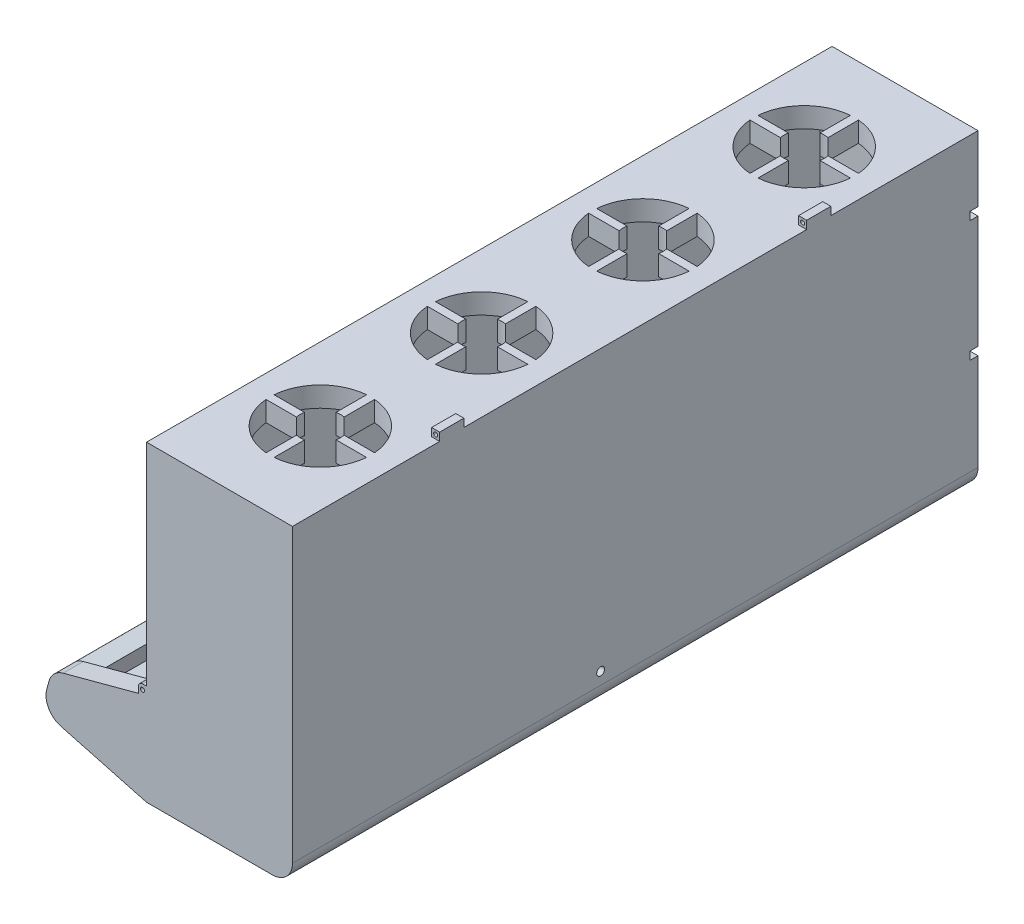
SolidWorks part; units mm, degrees
ref_plane "Front Plane" through (0, 0, 0) normal (0, 0, 1) x (1, 0, 0)
ref_plane "Top Plane" through (0, 0, 0) normal (0, 1, 0) x (1, 0, 0)
ref_plane "Right Plane" through (0, 0, 0) normal (1, 0, 0) x (0, 0, -1)
sketch "Sketch1" plane through (0, 0, 0) normal (0, 0, 1) x (1, 0, 0)
  line L16 (0, 0) -> (0, 25)
  line L17 (0, 25) -> (-15.5956, 25)
  line L18 (0, 0) -> (-15.5956, -9.0041)
  line L19 (-15.5956, 25) -> (-15.5956, 27.5)
  line L20 (-15.5956, 27.5) -> (2.5, 27.5)
  line L21 (2.5, 27.5) -> (2.5, -1.4434)
  line L22 (2.5, -1.4434) -> (-14.3456, -11.1692)
  line L23 (-14.3456, -11.1692) -> (-15.5956, -9.0041)
  line L24 (-15.5956, -9.0041) -> (-15.5956, 25) construction
  dimension "D1" = 25
  dimension "D2" = 120
  dimension "D3" = 2.5
  dimension "D4" = 2.5
  dimension "D5" = 2.5
extrude "Boss-Extrude1" add sketch "Sketch1" along normal blind 80
sketch "Sketch2" plane through (0, 27.5, 0) normal (0, 1, 0) x (1, 0, 0)
  line L0 (-6.5478, -10) -> (-6.5478, 0) construction
  line L1 (2.5, 0) -> (-15.5956, 0) construction
  line L2 (2.5, -80) -> (-15.5956, -80) construction
  circle A0 centre (-6.5478, -10) radius 2.5
  circle A1 centre (-6.5478, -30) radius 2.5
  circle A2 centre (-6.5478, -50) radius 2.5
  circle A3 centre (-6.5478, -70) radius 2.5
  dimension "D1" = 5
  dimension "D2" = 10
  dimension "D4" = 10
  dimension "D3" = 4
extrude "Cut-Extrude1" cut sketch "Sketch2" against normal up to surface (2.5 mm away) up to face at (-7.7978, 25, 40)
sketch "Sketch3" plane through (0, 0, 0) normal (0, 0, -1) x (-1, 0, 0)
  line L0 (15.5956, 25) -> (15.5956, -9.0041)
  line L1 (15.5956, -9.0041) -> (15.5956, -11.1692)
  line L2 (15.5956, -11.1692) -> (14.3456, -11.1692)
  line L8 (15.5956, -9.0041) -> (0, 0)
  line L9 (0, 0) -> (0, 25)
  line L10 (0, 25) -> (15.5956, 25)
  line L11 (15.5956, 25) -> (15.5956, 27.5)
  line L12 (15.5956, 27.5) -> (-2.5, 27.5)
  line L13 (-2.5, 27.5) -> (-2.5, -1.4434)
  line L14 (-2.5, -1.4434) -> (14.3456, -11.1692)
  line L15 (14.3456, -11.1692) -> (15.5956, -9.0041)
  line L19 (15.5956, 25) -> (15.5956, 27.5)
  line L20 (15.5956, 27.5) -> (-2.5, 27.5)
  line L21 (-2.5, 27.5) -> (-2.5, -1.4434)
  line L22 (-2.5, -1.4434) -> (14.3456, -11.1692)
  dimension "D1" = 0
extrude "Boss-Extrude2" add sketch "Sketch3" along normal blind 2.5
sketch "Sketch4" plane through (0, 0, 80) normal (0, 0, 1) x (1, 0, 0)
  line L0 (-15.5956, 25) -> (-15.5956, -9.0041)
  line L1 (-15.5956, -9.0041) -> (-15.5956, -11.1692)
  line L2 (-15.5956, -11.1692) -> (-14.3456, -11.1692)
  line L8 (0, 0) -> (-15.5956, -9.0041)
  line L9 (-15.5956, -9.0041) -> (-14.3456, -11.1692)
  line L10 (-14.3456, -11.1692) -> (2.5, -1.4434)
  line L11 (2.5, -1.4434) -> (2.5, 27.5)
  line L12 (2.5, 27.5) -> (-15.5956, 27.5)
  line L13 (-15.5956, 27.5) -> (-15.5956, 25)
  line L14 (-15.5956, 25) -> (0, 25)
  line L15 (0, 25) -> (0, 0)
  line L18 (-14.3456, -11.1692) -> (2.5, -1.4434)
  line L19 (2.5, -1.4434) -> (2.5, 27.5)
  line L20 (2.5, 27.5) -> (-15.5956, 27.5)
  line L21 (-15.5956, 27.5) -> (-15.5956, 25)
  dimension "D1" = 0
extrude "Boss-Extrude3" add sketch "Sketch4" along normal blind 2.5
sketch "Sketch6" plane through (0, 0, -2.5) normal (0, 0, -1) x (-1, 0, 0)
  line L0 (14.3456, -11.1692) -> (-2.5, -11.1692)
  line L1 (-2.5, -11.1692) -> (-2.5, -1.4434)
  line L2 (14.3456, -11.1692) -> (-2.5, -1.4434)
extrude "Boss-Extrude4" add sketch "Sketch6" against normal blind 2.5
sketch "Sketch7" plane through (0, 0, 82.5) normal (0, 0, 1) x (1, 0, 0)
  line L3 (2.5, -1.4434) -> (-14.3456, -11.1692)
  line L4 (-14.3456, -11.1692) -> (2.5, -11.1692)
  line L5 (2.5, -11.1692) -> (2.5, -1.4434)
  line L6 (2.5, -1.4434) -> (-14.3456, -11.1692)
  line L7 (-14.3456, -11.1692) -> (2.5, -11.1692)
  line L8 (2.5, -11.1692) -> (2.5, -1.4434)
  dimension "D1" = 0
extrude "Boss-Extrude5" add sketch "Sketch7" against normal blind 2.5
sketch "Sketch9" plane through (0, -11.1692, 0) normal (0, -1, 0) x (1, 0, 0)
  line L1 (-14.3456, -2.5) -> (2.5, -2.5)
  line L2 (-14.3456, -2.5) -> (-14.3456, 82.5)
  line L3 (-14.3456, 82.5) -> (2.5, 82.5)
  line L4 (2.5, -2.5) -> (2.5, 82.5)
extrude "Boss-Extrude10" add sketch "Sketch9" against normal blind 2.5
sketch "Sketch10" plane through (0, -8.6692, 0) normal (0, 1, 0) x (1, 0, 0)
  line L0 (-2.6549, -0.606) -> (-0.5, -0.606)
  line L1 (-3.1549, -0.106) -> (0, -0.106)
  line L2 (-3.1549, -0.106) -> (-3.1549, -41.3652)
  line L3 (-3.1549, -41.3652) -> (0, -41.3652)
  line L4 (0, -0.106) -> (0, -41.3652)
  line L17 (-0.5, -0.606) -> (-0.5, -40.8652)
  line L18 (-2.6549, -40.8652) -> (-0.5, -40.8652)
  line L19 (-2.6549, -0.606) -> (-2.6549, -40.8652)
  dimension "D1" = 0.5
sketch "Sketch12" plane through (0, 27.5, 0) normal (0, 1, 0) x (1, 0, 0)
  line L4 (2.5, -82.5) -> (2.5, 2.5)
  line L5 (2.5, 2.5) -> (-15.5956, 2.5)
  line L6 (-15.5956, 2.5) -> (-15.5956, -82.5)
  line L7 (-15.5956, -82.5) -> (2.5, -82.5)
  line L8 (2.5, -82.5) -> (2.5, 2.5)
  line L9 (2.5, 2.5) -> (-15.5956, 2.5)
  line L10 (-15.5956, 2.5) -> (-15.5956, -82.5)
  line L11 (-15.5956, -82.5) -> (2.5, -82.5)
  line L16 (0.5, -80.5) -> (0.5, 0.5)
  line L17 (0.5, 0.5) -> (-13.5956, 0.5)
  line L18 (-13.5956, 0.5) -> (-13.5956, -80.5)
  line L19 (-13.5956, -80.5) -> (0.5, -80.5)
  line L20 (0.5, -80.5) -> (0.5, 0.5)
  line L21 (0.5, 0.5) -> (-13.5956, 0.5)
  line L22 (-13.5956, 0.5) -> (-13.5956, -80.5)
  line L23 (-13.5956, -80.5) -> (0.5, -80.5)
  dimension "D1" = 0
  dimension "D2" = 2
extrude "Boss-Extrude13" add sketch "Sketch12" along normal blind 12.5
sketch "Sketch13" plane through (0, 40, 0) normal (0, 1, 0) x (1, 0, 0)
  line L4 (-15.5956, -82.5) -> (2.5, -82.5)
  line L5 (2.5, -82.5) -> (2.5, 2.5)
  line L6 (2.5, 2.5) -> (-15.5956, 2.5)
  line L7 (-15.5956, 2.5) -> (-15.5956, -82.5)
  line L8 (-15.5956, -82.5) -> (2.5, -82.5)
  line L9 (2.5, -82.5) -> (2.5, 2.5)
  line L10 (2.5, 2.5) -> (-15.5956, 2.5)
  line L11 (-15.5956, 2.5) -> (-15.5956, -82.5)
  dimension "D1" = 0
extrude "Boss-Extrude14" add sketch "Sketch13" along normal blind 2.5
sketch "Sketch15" plane through (0, 0, 80) normal (0, 0, -1) x (-1, 0, 0)
  line L3 (15.5956, -11.1692) -> (15.5956, -9.0041)
  line L4 (15.5956, -9.0041) -> (14.3456, -11.1692)
  line L5 (14.3456, -11.1692) -> (15.5956, -11.1692)
  line L6 (15.5956, -11.1692) -> (15.5956, -9.0041)
  line L7 (15.5956, -9.0041) -> (14.3456, -11.1692)
  line L8 (14.3456, -11.1692) -> (15.5956, -11.1692)
  dimension "D1" = 0
extrude "Boss-Extrude15" add sketch "Sketch15" along normal up to surface (80 mm away) up to face at (-7.7978, 10.249, 0)
sketch "Sketch16" plane through (0, 0, -2.5) normal (0, 0, -1) x (-1, 0, 0)
  line L0 (15.5956, -11.1692) -> (28.6248, -7.678)
  line L1 (28.6248, -7.678) -> (27.9778, -5.2632)
  line L2 (27.9778, -5.2632) -> (15.5956, -8.581)
  line L3 (15.5956, -8.581) -> (15.5956, -11.1692)
  line L4 (15.5956, -11.1692) -> (15.5956, 42.5) construction
  dimension "D1" = 2.5
  dimension "D2" = 75
extrude "Boss-Extrude16" add sketch "Sketch16" against normal up to surface (85 mm away)
sketch "Sketch17" plane through (0, 0, -2.5) normal (0, 0, -1) x (-1, 0, 0)
  line L0 (27.9778, -5.2632) -> (27.3307, -2.8484)
  line L1 (27.3307, -2.8484) -> (24.9159, -3.4954)
  line L2 (24.9159, -3.4954) -> (25.563, -5.9102)
  line L3 (27.9778, -5.2632) -> (15.5956, -8.581) construction
  line L4 (25.563, -5.9102) -> (27.9778, -5.2632)
  line L5 (28.6248, -7.678) -> (27.9778, -5.2632) construction
  dimension "D1" = 2.5
  dimension "D2" = 2.5
extrude "Boss-Extrude17" add sketch "Sketch17" against normal up to surface (85 mm away)
sketch "Sketch18" plane through (0, 0, -2.5) normal (0, 0, -1) x (-1, 0, 0)
  line L0 (27.3307, -2.8484) -> (15.5956, 0.296)
  line L1 (15.5956, -8.581) -> (15.5956, 42.5) construction
  line L2 (15.5956, 0.296) -> (15.5956, -8.581)
  line L3 (15.5956, -8.581) -> (25.563, -5.9102)
  line L4 (25.563, -5.9102) -> (24.9159, -3.4954)
  line L5 (24.9159, -3.4954) -> (27.3307, -2.8484)
  dimension "D1" = 75
extrude "Boss-Extrude18" add sketch "Sketch18" against normal blind 2.5
sketch "Sketch19" plane through (0, 0, 82.5) normal (0, 0, 1) x (1, 0, 0)
  line L5 (-15.5956, 0.296) -> (-27.3307, -2.8484)
  line L6 (-15.5956, -8.581) -> (-15.5956, 0.296)
  line L7 (-25.563, -5.9102) -> (-15.5956, -8.581)
  line L8 (-24.9159, -3.4954) -> (-25.563, -5.9102)
  line L9 (-27.3307, -2.8484) -> (-24.9159, -3.4954)
  line L10 (-15.5956, 0.296) -> (-27.3307, -2.8484)
  line L11 (-15.5956, -8.581) -> (-15.5956, 0.296)
  line L12 (-25.563, -5.9102) -> (-15.5956, -8.581)
  line L13 (-24.9159, -3.4954) -> (-25.563, -5.9102)
  line L14 (-27.3307, -2.8484) -> (-24.9159, -3.4954)
  dimension "D1" = 0
extrude "Boss-Extrude19" add sketch "Sketch19" against normal blind 2.5
extrude "Boss-Extrude21" add sketch "Sketch10" along normal blind 2.5
sketch "Sketch23" plane through (0, -6.1692, 0) normal (0, 1, 0) x (1, 0, 0)
  line L4 (-3.1549, -0.106) -> (-3.1549, -41.3652)
  line L5 (-3.1549, -41.3652) -> (0, -41.3652)
  line L6 (0, -41.3652) -> (0, -0.106)
  line L7 (0, -0.106) -> (-3.1549, -0.106)
  line L8 (-3.1549, -0.106) -> (-3.1549, -41.3652)
  line L9 (-3.1549, -41.3652) -> (0, -41.3652)
  line L10 (0, -41.3652) -> (0, -0.106)
  line L11 (0, -0.106) -> (-3.1549, -0.106)
  dimension "D1" = 0
extrude "Boss-Extrude22" add sketch "Sketch23" along normal blind 0.5
sketch "Sketch24" plane through (0, 0, 0) normal (1, 0, 0) x (0, 0, -1)
  line L4 (-41.3652, -8.6692) -> (-0.106, -8.6692)
  line L5 (-0.106, -8.6692) -> (-0.106, -5.6692)
  line L6 (-0.106, -5.6692) -> (-41.3652, -5.6692)
  line L7 (-41.3652, -5.6692) -> (-41.3652, -8.6692)
  line L8 (-41.3652, -8.6692) -> (-0.106, -8.6692)
  line L9 (-0.106, -8.6692) -> (-0.106, -5.6692)
  line L10 (-0.106, -5.6692) -> (-41.3652, -5.6692)
  line L11 (-41.3652, -5.6692) -> (-41.3652, -8.6692)
  dimension "D1" = 0
extrude "Cut-Extrude4" cut sketch "Sketch24" against normal blind 0.5
sketch "Sketch25" plane through (-2.6549, 0, 0) normal (1, 0, 0) x (0, 0, -1)
  line L0 (-40.8652, -6.1692) -> (-40.8652, -8.6692) construction
  line L1 (-0.606, -8.6692) -> (-40.8652, -8.6692)
  line L2 (-0.606, -8.6692) -> (-0.606, -8.1692)
  line L3 (-0.606, -8.1692) -> (-40.8652, -8.1692)
  line L4 (-40.8652, -8.6692) -> (-40.8652, -8.1692)
  dimension "D1" = 0.5
extrude "Boss-Extrude23" add sketch "Sketch25" along normal up to surface (2.1549 mm away) up to face at (-0.5, -7.2942, 20.7356)
sketch "Sketch26" plane through (-0.5, 0, 0) normal (1, 0, 0) x (0, 0, -1)
  line L0 (-20.7356, -6.1692) -> (-20.7356, -8.1692) construction
  line L1 (-0.606, -6.1692) -> (-40.8652, -6.1692) construction
  line L2 (-0.606, -8.1692) -> (-40.8652, -8.1692) construction
  line L4 (-20.9278, -8.1692) -> (-20.5158, -8.1692)
  line L5 (-20.9278, -8.1692) -> (-20.9278, -7.9938)
  line L6 (-20.9278, -7.9938) -> (-20.5158, -7.9938)
  line L7 (-20.5158, -8.1692) -> (-20.5158, -7.9938)
extrude "Boss-Extrude24" add sketch "Sketch26" against normal up to surface (2.1549 mm away) up to face at (-2.6549, -7.1692, 20.7356)
sketch "Sketch27" plane through (0, 0, 0.606) normal (0, 0, 1) x (1, 0, 0)
  circle A0 centre (-1.1714, -7.4121) radius 0.5386
extrude "Boss-Extrude25" add sketch "Sketch27" along normal blind 0.25
sketch "Sketch28" plane through (0, 0, 40.8652) normal (0, 0, -1) x (-1, 0, 0)
  line L1 (0.411, -6.8481) -> (1.6695, -6.8481)
  line L2 (0.411, -6.8481) -> (0.411, -7.9194)
  line L3 (0.411, -7.9194) -> (1.6695, -7.9194)
  line L4 (1.6695, -6.8481) -> (1.6695, -7.9194)
extrude "Boss-Extrude26" add sketch "Sketch28" along normal blind 0.25
sketch "Sketch29" plane through (-0.5, 0, 0) normal (1, 0, 0) x (0, 0, -1)
  line L0 (-0.606, -6.1692) -> (-40.8652, -6.1692)
  line L1 (-40.8652, -6.1692) -> (-40.8652, -8.1692)
  line L2 (-40.8652, -8.1692) -> (-0.606, -8.1692)
  line L3 (-0.606, -8.1692) -> (-0.606, -6.1692)
  line L4 (-41.3652, -8.6692) -> (-0.106, -8.6692)
  line L5 (-0.106, -8.6692) -> (-0.106, -5.6692)
  line L6 (-0.106, -5.6692) -> (-41.3652, -5.6692)
  line L7 (-41.3652, -5.6692) -> (-41.3652, -8.6692)
  line L8 (-41.3652, -8.6692) -> (-0.106, -8.6692)
  line L9 (-0.106, -8.6692) -> (-0.106, -5.6692)
  line L10 (-0.106, -5.6692) -> (-41.3652, -5.6692)
  line L11 (-41.3652, -5.6692) -> (-41.3652, -8.6692)
  dimension "D1" = 0
  dimension "D2" = 0.5
extrude "Boss-Extrude27" add sketch "Sketch29" along normal blind 1.25
sketch "Sketch31" plane through (2.5, 0, 0) normal (1, 0, 0) x (0, 0, -1)
  line L1 (-80, -1.4434) -> (0, -1.4434)
  line L2 (-80, -1.4434) -> (-80, -8.6692)
  line L3 (-80, -8.6692) -> (0, -8.6692)
  line L4 (0, -1.4434) -> (0, -8.6692)
sketch "Sketch32" plane through (0, -8.6692, 0) normal (0, 1, 0) x (1, 0, 0)
  line L1 (-5.5507, -49.6825) -> (0, -49.6825)
  line L2 (-5.5507, -49.6825) -> (-5.5507, -76.0243)
  line L3 (-5.5507, -76.0243) -> (0, -76.0243)
  line L4 (0, -49.6825) -> (0, -76.0243)
extrude "Boss-Extrude28" add sketch "Sketch32" along normal blind 0.5
sketch "Sketch33" plane through (0, -8.1692, 0) normal (0, 1, 0) x (1, 0, 0)
  line L1 (-3.0223, -50.6363) -> (-1.4068, -50.6363)
  line L2 (-3.0223, -50.6363) -> (-3.0223, -53.4267)
  line L3 (-3.0223, -53.4267) -> (-1.4068, -53.4267)
  line L4 (-1.4068, -50.6363) -> (-1.4068, -53.4267)
  line L5 (-3.0223, -54.6751) -> (-1.4068, -54.6751)
  line L6 (-3.0223, -54.6751) -> (-3.0223, -58.4937)
  line L7 (-3.0223, -58.4937) -> (-1.4068, -58.4937)
  line L8 (-1.4068, -54.6751) -> (-1.4068, -58.4937)
  line L9 (-3.0223, -60.2561) -> (-1.4068, -60.2561)
  line L10 (-3.0223, -60.2561) -> (-3.0223, -64.4418)
  line L11 (-3.0223, -64.4418) -> (-1.4068, -64.4418)
  line L12 (-1.4068, -60.2561) -> (-1.4068, -64.4418)
  line L13 (-3.0223, -66.5714) -> (-1.4068, -66.5714)
  line L14 (-3.0223, -66.5714) -> (-3.0223, -70.2431)
  line L15 (-3.0223, -70.2431) -> (-1.4068, -70.2431)
  line L16 (-1.4068, -66.5714) -> (-1.4068, -70.2431)
extrude "Boss-Extrude29" add sketch "Sketch33" along normal blind 0.25
extrude "Boss-Extrude30" add sketch "Sketch31" against normal blind 0.25
sketch "Sketch34" plane through (0, 0, 0) normal (0, 0, 1) x (1, 0, 0)
  line L1 (-15.5956, 25) -> (-14.5956, 25)
  line L2 (-15.5956, 25) -> (-15.5956, 0.296)
  line L3 (-15.5956, 0.296) -> (-14.5956, 0.296)
  line L4 (-14.5956, 25) -> (-14.5956, 0.296)
  dimension "D1" = 1
extrude "Boss-Extrude31" add sketch "Sketch34" along normal up to surface (80 mm away) separate body up to face at (-15.5769, 2.273, 80)
sketch "Sketch38" plane through (0, 0, -2.5) normal (0, 0, -1) x (-1, 0, 0)
  line L0 (-2.5, 40) -> (-2.5, 42.5)
  line L1 (-2.5, 42.5) -> (-2.5, -11.1692) construction
  line L2 (-2.5, 42.5) -> (0, 42.5)
  line L3 (-2.5, 42.5) -> (15.5956, 42.5) construction
  line L4 (13.0956, 42.5) -> (15.5956, 42.5)
  line L5 (15.5956, 42.5) -> (15.5956, 40)
  line L6 (15.5956, 0.296) -> (15.5956, 42.5) construction
  line L7 (26.21, -8.3251) -> (28.6248, -7.678)
  line L8 (15.5956, -11.1692) -> (28.6248, -7.678) construction
  line L9 (28.6248, -7.678) -> (27.9778, -5.2632)
  line L10 (28.6248, -7.678) -> (27.3307, -2.8484) construction
  line L11 (25.9365, -2.4748) -> (27.3307, -2.8484)
  line L12 (27.3307, -2.8484) -> (15.5956, 0.296) construction
  line L13 (27.3307, -2.8484) -> (27.7043, -4.2426)
  arc A0 (0, 42.5) -> (-2.5, 40) centre (0, 40) ccw
  arc A1 (15.5956, 40) -> (13.0956, 42.5) centre (13.0956, 40) ccw
  arc A2 (27.9778, -5.2632) -> (26.21, -8.3251) centre (25.563, -5.9102) cw
  arc A3 (27.7043, -4.2426) -> (25.9365, -2.4748) centre (25.2895, -4.8896) ccw
  dimension "D1" = 2.5
  dimension "D2" = 2.5
  dimension "D3" = 2.5
  dimension "D4" = 2.5
extrude "Cut-Extrude6" cut sketch "Sketch38" against normal up to surface (85 mm away) up to face at (-13.9632, 7.4902, 82.5)
sketch "Sketch39" plane through (0, 0, -2.5) normal (0, 0, -1) x (-1, 0, 0)
  line L0 (-2.5, 27.5) -> (15.5956, 27.5)
  line L7 (13.0956, 42.5) -> (0, 42.5)
  line L8 (-2.5, 40) -> (-2.5, -11.1692)
  line L9 (-2.5, -11.1692) -> (15.5956, -11.1692)
  line L10 (15.5956, -11.1692) -> (26.21, -8.3251)
  line L11 (27.9778, -5.2632) -> (27.7043, -4.2426)
  line L12 (25.9365, -2.4748) -> (15.5956, 0.296)
  line L13 (15.5956, 0.296) -> (15.5956, 40)
  line L14 (13.0956, 42.5) -> (0, 42.5)
  line L15 (-2.5, 40) -> (-2.5, 27.5)
  line L20 (15.5956, 27.5) -> (15.5956, 40)
  arc A4 (0, 42.5) -> (-2.5, 40) centre (0, 40) ccw
  arc A5 (26.21, -8.3251) -> (27.9778, -5.2632) centre (25.563, -5.9102) ccw
  arc A6 (27.7043, -4.2426) -> (25.9365, -2.4748) centre (25.2895, -4.8896) ccw
  arc A7 (15.5956, 40) -> (13.0956, 42.5) centre (13.0956, 40) ccw
  arc A8 (0, 42.5) -> (-2.5, 40) centre (0, 40) ccw
  arc A11 (15.5956, 40) -> (13.0956, 42.5) centre (13.0956, 40) ccw
  dimension "D2" = 15
  dimension "D1" = 0
extrude "Cut-Extrude7" cut sketch "Sketch39" against normal up to surface (85 mm away) up to face at (-14.8711, 11.2326, 82.5)
sketch "Sketch40" plane through (2.5, 0, 0) normal (1, 0, 0) x (0, 0, -1)
  line L5 (-82.5, 27.5) -> (2.5, 27.5) construction
  line L10 (-64.25, 28.5) -> (-61.25, 28.5)
  line L11 (-64.25, 28.5) -> (-64.25, 27.5)
  line L12 (-64.25, 27.5) -> (-61.25, 27.5)
  line L13 (-61.25, 28.5) -> (-61.25, 27.5)
  line L14 (-61.25, 28.5) -> (-18.75, 28.5) construction
  line L15 (-18.75, 28.5) -> (-15.75, 28.5)
  line L16 (-18.75, 28.5) -> (-18.75, 27.5)
  line L17 (-18.75, 27.5) -> (-15.75, 27.5)
  line L18 (-15.75, 28.5) -> (-15.75, 27.5)
  line L19 (-40, 27.5) -> (-40, 28.5) construction
  dimension "D1" = 1
  dimension "D2" = 3
  dimension "D3" = 3
  dimension "D4" = 42.5
extrude "Boss-Extrude32" add sketch "Sketch40" against normal blind 1
sketch "Sketch41" plane through (0, 0, 15.75) normal (0, 0, -1) x (-1, 0, 0)
  line L0 (-2.5, 28) -> (-2, 28) construction
  line L1 (-2.5, 27.5) -> (-2.5, 28.5) construction
  line L2 (-2, 28) -> (-2, 28.5) construction
  line L3 (-1.5, 28.5) -> (-2.5, 28.5) construction
  circle A0 centre (-2, 28) radius 0.25
  dimension "D1" = 0.5
extrude "Cut-Extrude8" cut sketch "Sketch41" against normal up to surface (48.5 mm away) up to face at (2, 28, 64.25)
sketch "Sketch42" plane through (0, 27.5, 0) normal (0, 1, 0) x (1, 0, 0)
  line L0 (-6.5478, -16.25) -> (-6.5478, -12.5) construction
  line L1 (2.5, 2.5) -> (-15.5956, 2.5) construction
  line L2 (-12.7978, -10) -> (-9.0478, -10) construction
  line L4 (-7.0478, -3.77) -> (-7.0478, -7.5505)
  line L6 (-6.0478, -3.77) -> (-6.0478, -7.5505)
  line L7 (-12.7778, -9.5) -> (-8.9973, -9.5)
  line L9 (-12.7778, -10.5) -> (-8.9973, -10.5)
  line L11 (-12.7778, -29.5) -> (-8.9973, -29.5)
  line L12 (-6.0478, -32.4495) -> (-6.0478, -36.23)
  line L13 (-12.7778, -30.5) -> (-8.9973, -30.5)
  line L14 (-7.0478, -23.77) -> (-7.0478, -27.5505)
  line L15 (-6.0478, -23.77) -> (-6.0478, -27.5505)
  line L16 (-12.7778, -49.5) -> (-8.9973, -49.5)
  line L17 (-4.0478, -70) -> (-0.2978, -70) construction
  line L18 (-12.7778, -50.5) -> (-8.9973, -50.5)
  line L19 (-7.0478, -43.77) -> (-7.0478, -47.5505)
  line L20 (-6.0478, -43.77) -> (-6.0478, -47.5505)
  line L21 (-12.7778, -69.5) -> (-8.9973, -69.5)
  line L22 (-12.7978, -70) -> (-9.0478, -70) construction
  line L23 (-12.7778, -70.5) -> (-8.9973, -70.5)
  line L24 (-7.0478, -63.77) -> (-7.0478, -67.5505)
  line L25 (-6.0478, -63.77) -> (-6.0478, -67.5505)
  line L26 (2.5, -82.5) -> (-15.5956, -82.5) construction
  line L27 (-4.0983, -29.5) -> (-0.3178, -29.5)
  line L28 (-7.0478, -30) -> (-6.0478, -30) construction
  line L29 (-4.0983, -30.5) -> (-0.3178, -30.5)
  line L30 (-7.0478, -32.4495) -> (-7.0478, -36.23)
  line L31 (-4.0983, -9.5) -> (-0.3178, -9.5)
  line L32 (-4.0478, -10) -> (-0.2978, -10) construction
  line L33 (-4.0983, -10.5) -> (-0.3178, -10.5)
  line L34 (-6.0478, -12.4495) -> (-6.0478, -16.23)
  line L35 (-6.5478, -7.5) -> (-6.5478, -3.75) construction
  line L36 (-7.0478, -12.4495) -> (-7.0478, -16.23)
  line L37 (-7.0478, -52.4495) -> (-7.0478, -56.23)
  line L38 (-6.0478, -52.4495) -> (-6.0478, -56.23)
  line L39 (-4.0983, -49.5) -> (-0.3178, -49.5)
  line L40 (-4.0983, -50.5) -> (-0.3178, -50.5)
  line L41 (-4.0983, -69.5) -> (-0.3178, -69.5)
  line L42 (-7.0478, -72.4495) -> (-7.0478, -76.23)
  line L43 (-6.0478, -72.4495) -> (-6.0478, -76.23)
  line L44 (-4.0983, -70.5) -> (-0.3178, -70.5)
  line L45 (-12.7978, -50) -> (-0.2978, -50) construction
  arc A0 (-12.7778, -10.5) -> (-7.0478, -16.23) centre (-6.5478, -10) ccw
  arc A1 (-7.0478, -23.77) -> (-12.7778, -29.5) centre (-6.5478, -30) ccw
  arc A2 (-0.3178, -49.5) -> (-6.0478, -43.77) centre (-6.5478, -50) ccw
  arc A3 (-7.0478, -63.77) -> (-12.7778, -69.5) centre (-6.5478, -70) ccw
  arc A4 (-6.0478, -16.23) -> (-0.3178, -10.5) centre (-6.5478, -10) ccw
  arc A5 (-7.0478, -3.77) -> (-12.7778, -9.5) centre (-6.5478, -10) ccw
  arc A6 (-0.3178, -9.5) -> (-6.0478, -3.77) centre (-6.5478, -10) ccw
  arc A7 (-0.3178, -29.5) -> (-6.0478, -23.77) centre (-6.5478, -30) ccw
  arc A8 (-12.7778, -30.5) -> (-7.0478, -36.23) centre (-6.5478, -30) ccw
  arc A9 (-6.0478, -36.23) -> (-0.3178, -30.5) centre (-6.5478, -30) ccw
  arc A10 (-12.7778, -70.5) -> (-7.0478, -76.23) centre (-6.5478, -70) ccw
  arc A11 (-6.0478, -76.23) -> (-0.3178, -70.5) centre (-6.5478, -70) ccw
  arc A12 (-0.3178, -69.5) -> (-6.0478, -63.77) centre (-6.5478, -70) ccw
  arc A13 (-6.0478, -56.23) -> (-0.3178, -50.5) centre (-6.5478, -50) ccw
  arc A14 (-12.7778, -50.5) -> (-7.0478, -56.23) centre (-6.5478, -50) ccw
  arc A15 (-7.0478, -43.77) -> (-12.7778, -49.5) centre (-6.5478, -50) ccw
  arc A16 (-7.0478, -7.5505) -> (-8.9973, -9.5) centre (-6.5478, -10) ccw
  arc A17 (-8.9973, -10.5) -> (-7.0478, -12.4495) centre (-6.5478, -10) ccw
  arc A18 (-6.0478, -12.4495) -> (-4.0983, -10.5) centre (-6.5478, -10) ccw
  arc A19 (-4.0983, -9.5) -> (-6.0478, -7.5505) centre (-6.5478, -10) ccw
  arc A20 (-7.0478, -27.5505) -> (-8.9973, -29.5) centre (-6.5478, -30) ccw
  arc A22 (-8.9973, -50.5) -> (-7.0478, -52.4495) centre (-6.5478, -50) ccw
  arc A23 (-6.0478, -72.4495) -> (-4.0983, -70.5) centre (-6.5478, -70) ccw
  arc A24 (-4.0983, -69.5) -> (-6.0478, -67.5505) centre (-6.5478, -70) ccw
  arc A25 (-8.9973, -70.5) -> (-7.0478, -72.4495) centre (-6.5478, -70) ccw
  arc A26 (-7.0478, -67.5505) -> (-8.9973, -69.5) centre (-6.5478, -70) ccw
  arc A27 (-7.0478, -47.5505) -> (-8.9973, -49.5) centre (-6.5478, -50) ccw
  arc A28 (-4.0983, -49.5) -> (-6.0478, -47.5505) centre (-6.5478, -50) ccw
  arc A29 (-6.0478, -52.4495) -> (-4.0983, -50.5) centre (-6.5478, -50) ccw
  arc A30 (-6.0478, -32.4495) -> (-4.0983, -30.5) centre (-6.5478, -30) ccw
  arc A31 (-8.9973, -30.5) -> (-7.0478, -32.4495) centre (-6.5478, -30) ccw
  arc A32 (-4.0983, -29.5) -> (-6.0478, -27.5505) centre (-6.5478, -30) ccw
  dimension "D1" = 12.5
  dimension "D2" = 1
  dimension "D3" = 1
  dimension "D4" = 12.5
  dimension "D6" = 12.5
  dimension "D5" = 4
extrude "Cut-Extrude10" cut sketch "Sketch42" against normal up to surface (2.5 mm away) up to face at (-9.0478, 25, 10)
sketch "Sketch43" plane through (0, 0, 80) normal (0, 0, -1) x (-1, 0, 0)
  line L0 (0, 11.0329) -> (0, 0)
  line L1 (0, 25) -> (0, 0) construction
  line L2 (0, 0) -> (9.5548, -5.5165)
  line L3 (0, 0) -> (15.5956, -9.0041) construction
  arc A0 (9.5548, -5.5165) -> (0, 11.0329) centre (19.1096, 11.0329) cw
extrude "Boss-Extrude33" add sketch "Sketch43" along normal up to surface (80 mm away) up to face at (-16.5712, 1.7915, 0)
sketch "Sketch51" plane through (2.5, 0, 0) normal (1, 0, 0) x (0, 0, -1)
  line L0 (-44.2876, -11.1692) -> (-44.2876, -7.1692) construction
  line L1 (-82.5, -11.1692) -> (2.5, -11.1692) construction
  circle A1 centre (-44.2876, -7.1692) radius 0.75
  dimension "D1" = 4
  dimension "D2" = 1.5
extrude "Cut-Extrude13" cut sketch "Sketch51" against normal blind 7.5 contours A1
sketch "Sketch52" plane through (2.5, 0, 0) normal (1, 0, 0) x (0, 0, -1)
  circle A0 centre (-44.2876, -7.1692) radius 0.75
  circle A1 centre (-44.2876, -7.1692) radius 0.4925
extrude "Boss-Extrude37" add sketch "Sketch52" against normal blind 2.5
sketch "Sketch53" plane through (0, 0, -2.5) normal (0, 0, -1) x (-1, 0, 0)
  line L0 (15.5956, 0.296) -> (15.5956, 1.296)
  line L1 (15.5956, 1.296) -> (16.5956, 1.296)
  line L2 (16.5956, 1.296) -> (16.5956, 0.0281)
  line L3 (25.9365, -2.4748) -> (15.5956, 0.296) construction
  line L4 (16.5956, 0.0281) -> (15.5956, 0.296)
  dimension "D1" = 1
  dimension "D2" = 1
extrude "Boss-Extrude38" add sketch "Sketch53" against normal blind 2.5
sketch "Sketch54" plane through (0, 0, 82.5) normal (0, 0, 1) x (1, 0, 0)
  line L4 (-15.5956, 0.296) -> (-15.5956, 1.296)
  line L5 (-15.5956, 1.296) -> (-16.5956, 1.296)
  line L6 (-16.5956, 1.296) -> (-16.5956, 0.0281)
  line L7 (-16.5956, 0.0281) -> (-15.5956, 0.296)
  line L8 (-15.5956, 0.296) -> (-15.5956, 1.296)
  line L9 (-15.5956, 1.296) -> (-16.5956, 1.296)
  line L10 (-16.5956, 1.296) -> (-16.5956, 0.0281)
  line L11 (-16.5956, 0.0281) -> (-15.5956, 0.296)
  dimension "D1" = 0
extrude "Boss-Extrude39" add sketch "Sketch54" against normal blind 2.5
sketch "Sketch55" plane through (0, 0, -2.5) normal (0, 0, -1) x (-1, 0, 0)
  line L0 (16.0956, 1.296) -> (16.0956, 0.6621) construction
  line L1 (16.5956, 1.296) -> (15.5956, 1.296) construction
  line L2 (16.0956, 0.6621) -> (16.5956, 0.6621) construction
  line L3 (16.5956, 0.0281) -> (16.5956, 1.296) construction
  line L4 (16.5956, 0.796) -> (16.5956, 1.296)
  line L5 (16.5956, 1.296) -> (16.0956, 1.296)
  circle A0 centre (16.0956, 0.6621) radius 0.25
  arc A1 (16.0956, 1.296) -> (16.5956, 0.796) centre (16.0956, 0.796) cw
  dimension "D1" = 0.5
extrude "Cut-Extrude15" cut sketch "Sketch55" against normal up to surface (85 mm away)
sketch "Sketch57" plane through (-15.5956, 0, 0) normal (-1, 0, 0) x (0, 0, 1)
  line L0 (-2.5, -11.1692) -> (-2.5, 3.8308) construction
  line L1 (-2.5, 1.296) -> (-2.5, 27.5) construction
  line L2 (-2.5, 3.8308) -> (-2.5, 18.8308) construction
  line L3 (-2.5, 4.3308) -> (-1.5, 4.3308)
  line L4 (-2.5, 4.3308) -> (-2.5, 3.3308)
  line L5 (-2.5, 3.3308) -> (-1.5, 3.3308)
  line L6 (-1.5, 4.3308) -> (-1.5, 3.3308)
  line L8 (-2.5, 19.3308) -> (-1.5, 19.3308)
  line L9 (-2.5, 19.3308) -> (-2.5, 18.3308)
  line L10 (-2.5, 18.3308) -> (-1.5, 18.3308)
  line L11 (-1.5, 19.3308) -> (-1.5, 18.3308)
  point P9 (-2.5, 3.8308)
  point P15 (-2.5, 18.8308)
  dimension "D1" = 15
  dimension "D2" = 1
  dimension "D3" = 1
  dimension "D4" = 15
  dimension "D5" = 1
  dimension "D6" = 1
extrude "Cut-Extrude16" cut sketch "Sketch57" against normal up to surface (18.0956 mm away) up to face at (2.5, 21.3885, 40)
sketch "Sketch58" plane through (0, 0, -2.5) normal (0, 0, -1) x (-1, 0, 0)
  line L0 (0, -11.1692) -> (-2.5, -11.1692)
  line L1 (-2.5, -11.1692) -> (15.5956, -11.1692) construction
  line L2 (-2.5, -11.1692) -> (-2.5, -8.6692)
  line L3 (-2.5, 3.3308) -> (-2.5, -11.1692) construction
  arc A0 (-2.5, -8.6692) -> (0, -11.1692) centre (0, -8.6692) ccw
  dimension "D1" = 2.5
extrude "Cut-Extrude17" cut sketch "Sketch58" against normal up to surface (85 mm away) up to face at (-16.6564, 1.3122, 82.5)
sketch "Sketch59" plane through (0, 0, -2.5) normal (0, 0, -1) x (-1, 0, 0)
  line L0 (1.6, -11.1692) -> (1.6, -4.6992) construction
  line L1 (0, -11.1692) -> (15.5956, -11.1692) construction
  line L2 (1.6, -4.6992) -> (-2.5, -4.6992) construction
  line L3 (-2.5, 3.3308) -> (-2.5, -8.6692) construction
  circle A0 centre (1.6, -4.6992) radius 0.5
  dimension "D1" = 4.1
  dimension "D3" = 1
  dimension "D2" = 6.47
extrude "Cut-Extrude18" cut sketch "Sketch59" against normal blind 4.5
